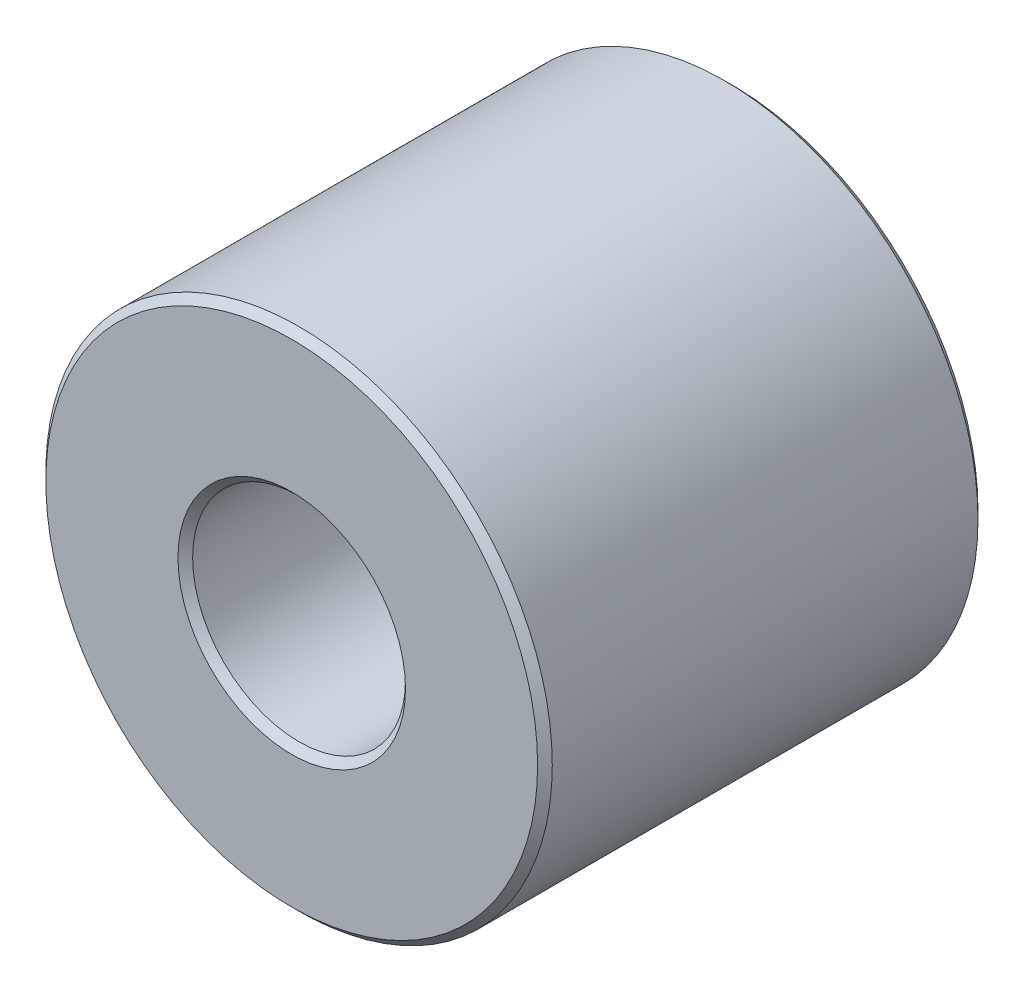
SolidWorks part; units mm, degrees
ref_plane "Front" through (0, 0, 0) normal (0, 0, 1) x (1, 0, 0)
ref_plane "Top" through (0, 0, 0) normal (0, 1, 0) x (1, 0, 0)
ref_plane "Right" through (0, 0, 0) normal (1, 0, 0) x (0, 0, -1)
sketch "Sketch1" plane through (0, 0, 0) normal (0, 0, 1) x (1, 0, 0)
  circle A0 centre (0, 0) radius 1.45
  circle A1 centre (0, 0) radius 3.45
  dimension "D1" = 2.9
  dimension "D2" = 2
extrude "Boss-Extrude1" add sketch "Sketch1" along normal blind 6
chamfer "Chamfer1" distance 0.1 angle 45 4 edges at (1.45, 0, 0) (1.45, 0, 6) (3.45, 0, 0) (3.45, 0, 6)
